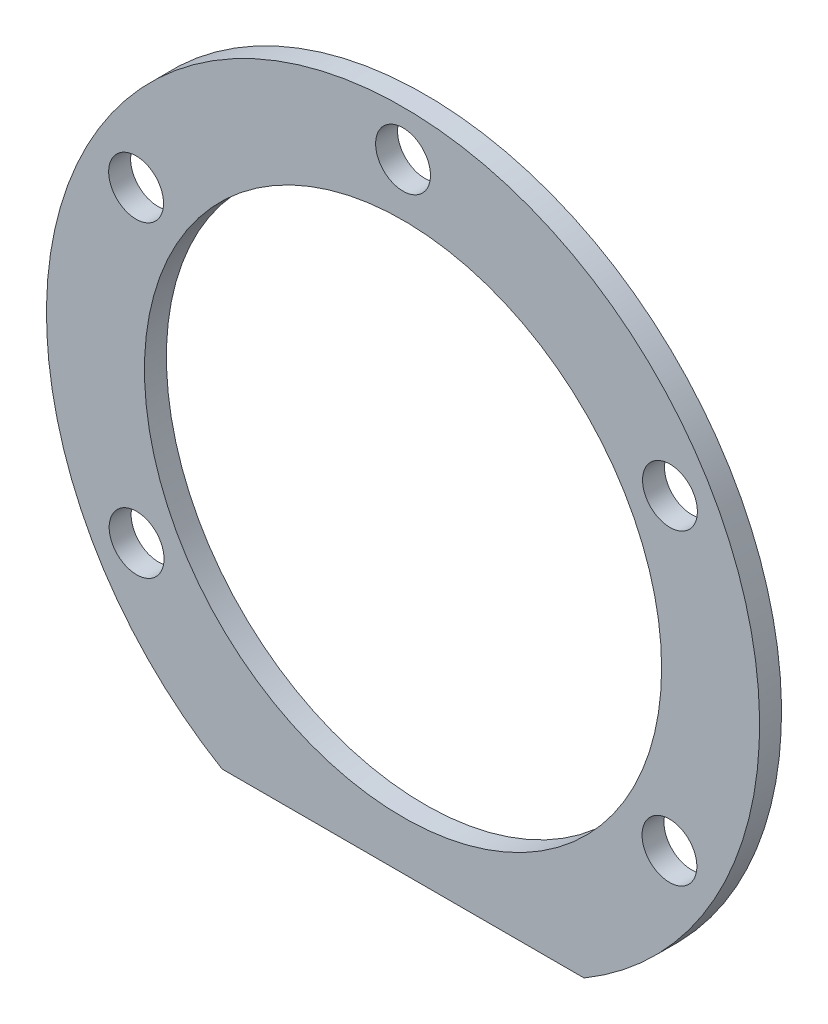
SolidWorks part; units mm, degrees
ref_plane "Front Plane" through (0, 0, 0) normal (0, 0, 1) x (1, 0, 0)
ref_plane "Top Plane" through (0, 0, 0) normal (0, 1, 0) x (1, 0, 0)
ref_plane "Right Plane" through (0, 0, 0) normal (1, 0, 0) x (0, 0, -1)
sketch "Sketch1" plane through (0, 0, 0) normal (0, 0, 1) x (1, 0, 0)
  line L0 (-16.5, -28) -> (16.5, -28)
  arc A0 (16.5, -28) -> (-16.5, -28) centre (0, 0) ccw
  circle A1 centre (0, 0) radius 23.57
  circle A2 centre (24.2833, -14.06) radius 2.5
  circle A3 centre (24.3295, 13.98) radius 2.5
  circle A4 centre (0, 28.3584) radius 2.5
  circle A5 centre (-24.3295, 13.98) radius 2.5
  circle A6 centre (-24.2833, -14.06) radius 2.5
  dimension "D1" = 65
  dimension "D2" = 47.14
  dimension "D4" = 13.94
  dimension "D5" = 28.04
  dimension "D6" = 28.06
  dimension "D7" = 28.06
  dimension "D8" = 28.06
  dimension "D9" = 28.06
  dimension "D3" = 33
extrude "Boss-Extrude1" add sketch "Sketch1" along normal blind 5
sketch "Sketch2" plane through (0, -28, 0) normal (0, -1, 0) x (-1, 0, 0)
  line L0 (-32.5, 0) -> (-32.5, -5) construction
  line L1 (32.5, 0) -> (-32.5, 0)
  line L2 (32.5, 0) -> (32.5, -3)
  line L3 (32.5, -3) -> (-32.5, -3)
  line L4 (-32.5, 0) -> (-32.5, -3)
  dimension "D1" = 3
extrude "Cut-Extrude1" cut sketch "Sketch2" against normal blind 70
